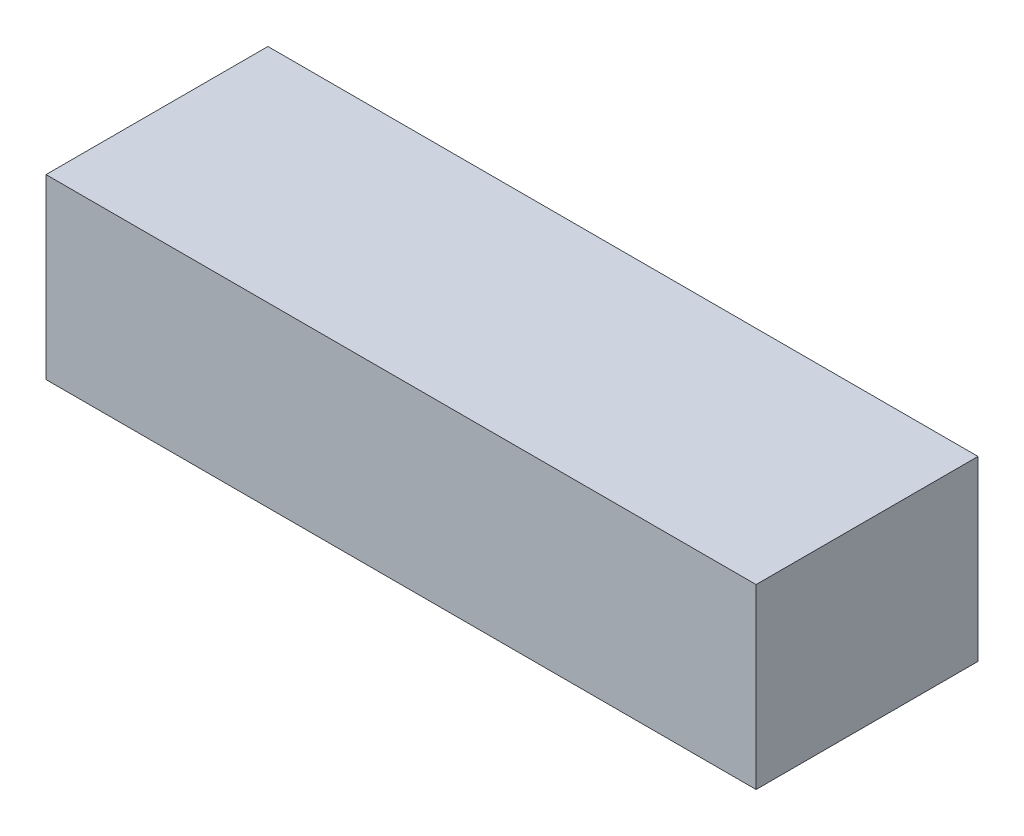
SolidWorks part; units mm, degrees
ref_plane "Front Plane" through (0, 0, 0) normal (0, 0, 1) x (1, 0, 0)
ref_plane "Top Plane" through (0, 0, 0) normal (0, 1, 0) x (1, 0, 0)
ref_plane "Right Plane" through (0, 0, 0) normal (1, 0, 0) x (0, 0, -1)
sketch "Sketch1" plane through (0, 0, 0) normal (0, 0, 1) x (1, 0, 0)
  line L1 (0, 0) -> (101.6, 0)
  line L2 (0, 0) -> (0, -25.4)
  line L3 (0, -25.4) -> (101.6, -25.4)
  line L4 (101.6, 0) -> (101.6, -25.4)
  dimension "D1" = 101.6
  dimension "D2" = 25.4
extrude "Boss-Extrude1" add sketch "Sketch1" along normal blind 31.75
